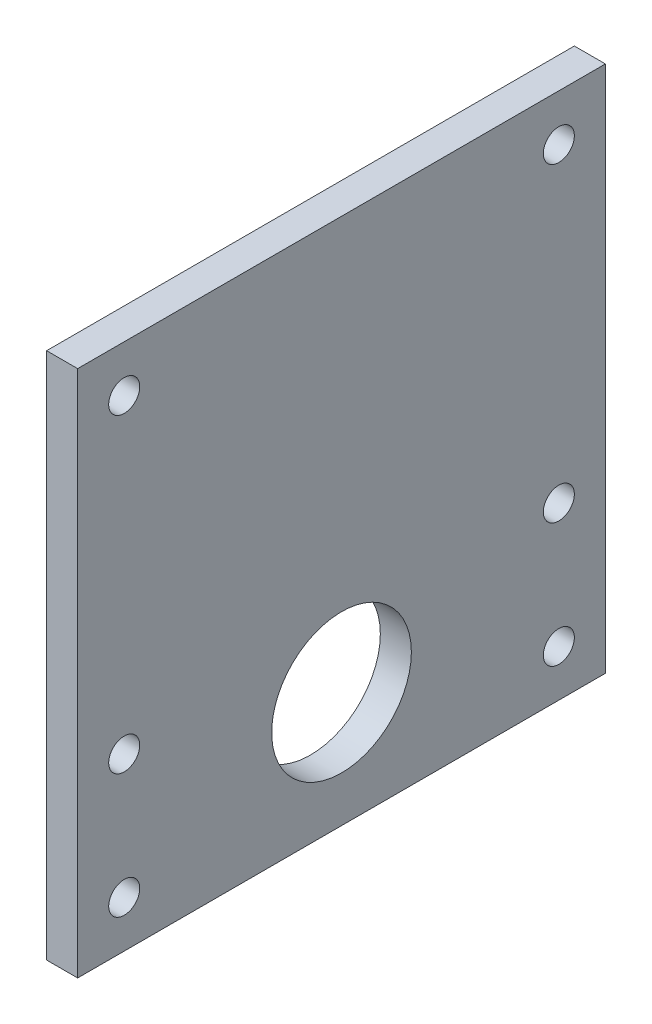
SolidWorks part; units mm, degrees
material "1060 Alloy"
ref_plane "Front Plane" through (0, 0, 0) normal (0, 0, 1) x (1, 0, 0)
ref_plane "Top Plane" through (0, 0, 0) normal (0, 1, 0) x (1, 0, 0)
ref_plane "Right Plane" through (0, 0, 0) normal (1, 0, 0) x (0, 0, -1)
sketch "Sketch1" plane through (0, 0, 0) normal (1, 0, 0) x (0, 0, -1)
  line L1 (-53.975, -53.975) -> (53.975, -53.975)
  line L2 (-53.975, -53.975) -> (-53.975, 53.975)
  line L3 (-53.975, 53.975) -> (53.975, 53.975)
  line L4 (53.975, -53.975) -> (53.975, 53.975)
  line L5 (-53.975, -53.975) -> (53.975, 53.975) construction
  line L6 (-53.975, 53.975) -> (53.975, -53.975) construction
  circle A2 centre (-44.45, 44.45) radius 3.175
  circle A3 centre (-44.45, -19.05) radius 3.175
  circle A4 centre (-44.45, -44.45) radius 3.175
  circle A5 centre (44.45, -44.45) radius 3.175
  circle A6 centre (44.45, -19.05) radius 3.175
  circle A7 centre (44.45, 44.45) radius 3.175
  circle A8 centre (0, -30.3575) radius 14.2875
  point P0 (0, 0)
  dimension "D2" = 6.35
  dimension "D3" = 28.575
  dimension "D1" = 107.95
extrude "Boss-Extrude1" add sketch "Sketch1" along normal mid plane 6.35
